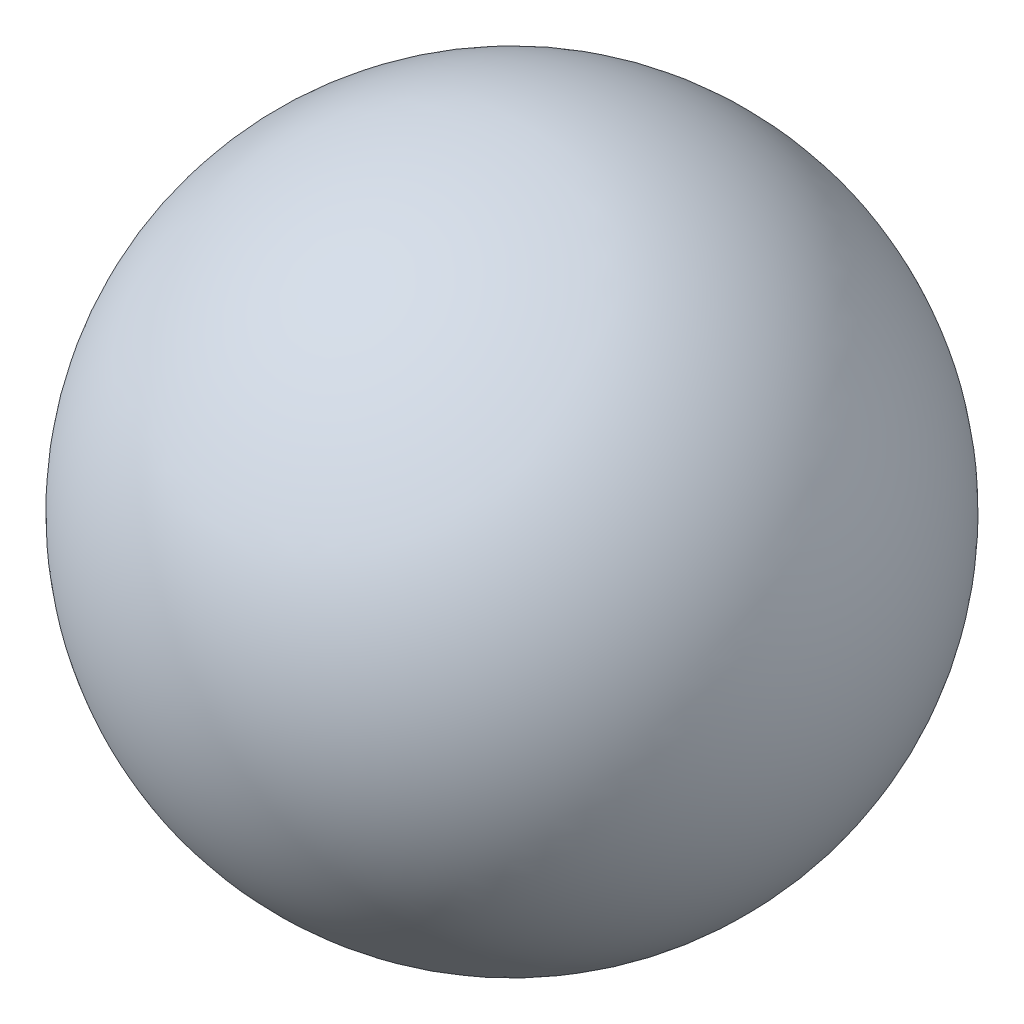
SolidWorks part; units mm, degrees
ref_plane "Front Plane" through (0, 0, 0) normal (0, 0, 1) x (1, 0, 0)
ref_plane "Top Plane" through (0, 0, 0) normal (0, 1, 0) x (1, 0, 0)
ref_plane "Right Plane" through (0, 0, 0) normal (1, 0, 0) x (0, 0, -1)
sketch "Sketch1" plane through (0, 0, 0) normal (0, 1, 0) x (1, 0, 0)
  line L0 (0, 25) -> (0, -25)
  arc A1 (0, 25) -> (0, -25) centre (0, 0) ccw
  point P1 (0, 0)
  point P4 (0, 0)
  point P5 (0, 0)
  point P6 (0, 0)
  point P7 (0, 0)
  point P8 (0, 0)
  dimension "D1" = 50
revolve "Revolve1" add sketch "Sketch1" angle 360 about L0
